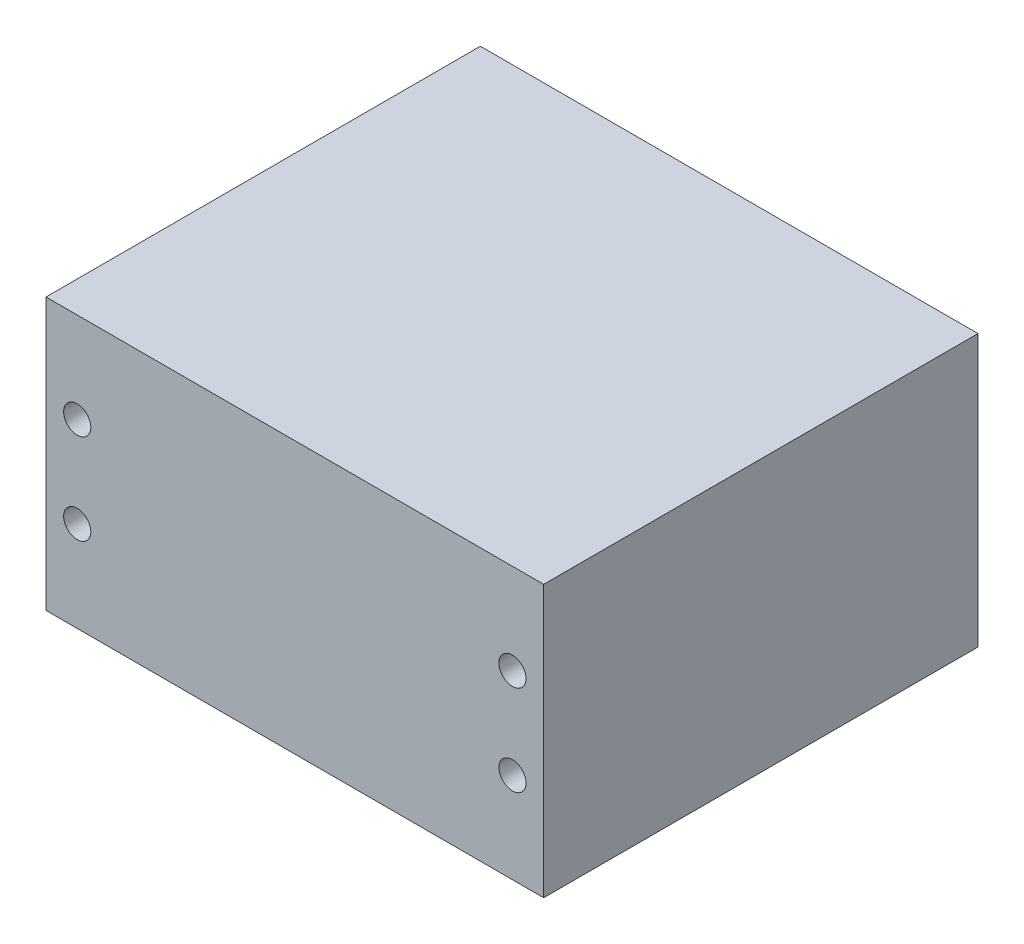
SolidWorks part; units mm, degrees
ref_plane "Front Plane" through (0, 0, 0) normal (0, 0, 1) x (1, 0, 0)
ref_plane "Top Plane" through (0, 0, 0) normal (0, 1, 0) x (1, 0, 0)
ref_plane "Right Plane" through (0, 0, 0) normal (1, 0, 0) x (0, 0, -1)
sketch "Sketch1" plane through (0, 0, 0) normal (0, 0, 1) x (1, 0, 0)
  line L0 (24.05, -5) -> (24.05, 5) construction
  line L1 (24.05, 0) -> (0, 0) construction
  line L2 (0, -55) -> (0, 55) construction
  line L4 (-27.5, 15) -> (27.5, 15)
  line L5 (-27.5, 15) -> (-27.5, -15)
  line L6 (-27.5, -15) -> (27.5, -15)
  line L7 (27.5, 15) -> (27.5, -15)
  line L8 (-27.5, 15) -> (27.5, -15) construction
  line L9 (-27.5, -15) -> (27.5, 15) construction
  circle A0 centre (24.05, 5) radius 1.5
  circle A1 centre (24.05, -5) radius 1.5
  circle A2 centre (-24.05, -5) radius 1.5
  circle A3 centre (-24.05, 5) radius 1.5
  dimension "D1" = 3
  dimension "D2" = 24.05
  dimension "D3" = 10
  dimension "D4" = 10
  dimension "D5" = 30
  dimension "D6" = 55
extrude "Boss-Extrude1" add sketch "Sketch1" along normal blind 48
sketch "Sketch2" plane through (0, 0, 48) normal (0, 0, 1) x (1, 0, 0)
  line L1 (-20.125, 10.125) -> (20.125, 10.125)
  line L2 (-20.125, 10.125) -> (-20.125, -10.125)
  line L3 (-20.125, -10.125) -> (20.125, -10.125)
  line L4 (20.125, 10.125) -> (20.125, -10.125)
  line L5 (-20.125, 10.125) -> (20.125, -10.125) construction
  line L6 (-20.125, -10.125) -> (20.125, 10.125) construction
  point P0 (0, 0)
  dimension "D1" = 40.25
  dimension "D2" = 20.25
